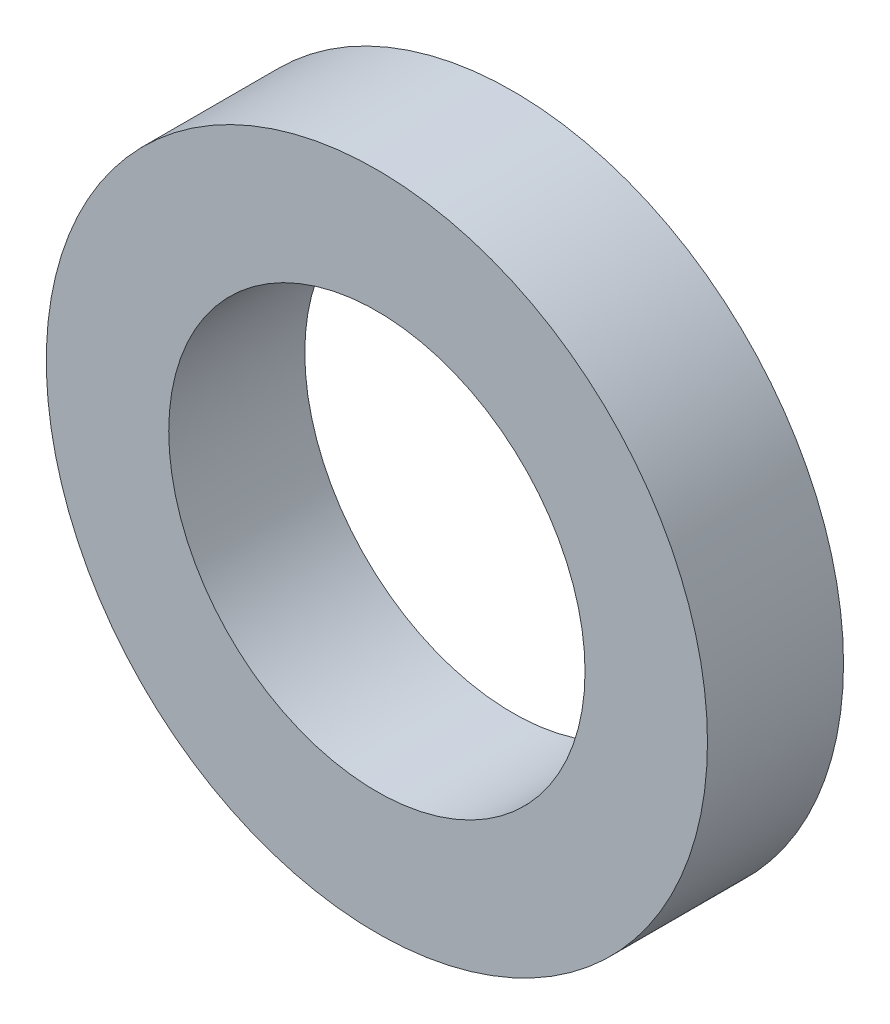
SolidWorks part; units mm, degrees
ref_plane "Спереди" through (0, 0, 0) normal (0, 0, 1) x (1, 0, 0)
ref_plane "Сверху" through (0, 0, 0) normal (0, 1, 0) x (1, 0, 0)
ref_plane "Справа" through (0, 0, 0) normal (1, 0, 0) x (0, 0, -1)
sketch "Эскиз1" plane through (0, 0, 0) normal (0, 0, 1) x (1, 0, 0)
  circle A0 centre (0, 0) radius 12.15
  circle A1 centre (0, 0) radius 7.65
  dimension "D1" = 24.3
  dimension "D2" = 15.3
extrude "Бобышка-Вытянуть1" add sketch "Эскиз1" along normal blind 5
